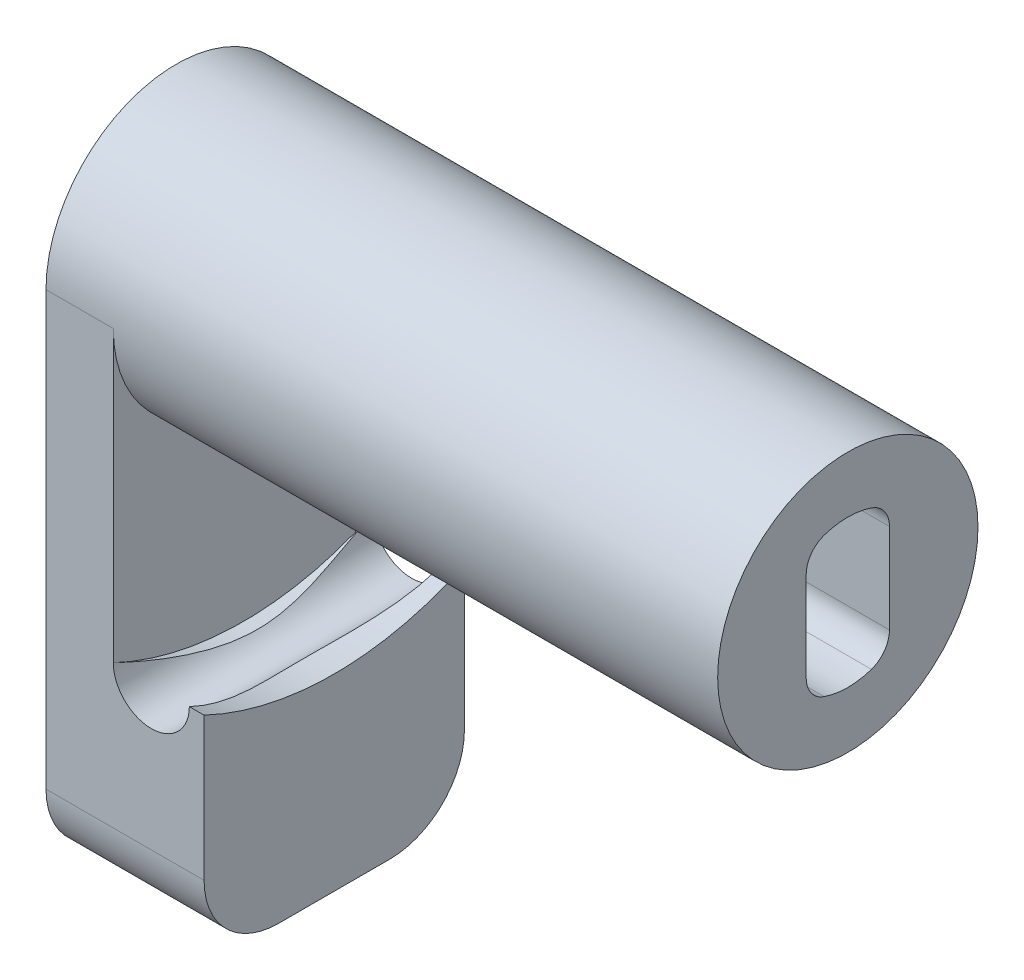
SolidWorks part; units mm, degrees
material "ABS"
ref_plane "Front Plane" through (0, 0, 0) normal (1, 0, 0) x (0, 1, 0)
ref_plane "Top Plane" through (0, 0, 0) normal (0, 0, 1) x (0, 1, 0)
ref_plane "Right Plane" through (0, 0, 0) normal (0, 1, 0) x (-1, 0, 0)
sketch "Sketch1" plane through (0, 0, 0) normal (1, 0, 0) x (0, 1, 0)
  circle A2 centre (0, 0) radius 8.7376
  dimension "D3" = 17.4752
extrude "Boss-Extrude1" add sketch "Sketch1" along normal blind 45.085
sketch "Sketch10" plane through (0, 0, 0) normal (-1, 0, 0) x (0, -1, 0)
  line L0 (0, 8.7376) -> (34.036, 8.7376)
  line L2 (34.036, 8.7376) -> (34.036, -8.7376)
  line L3 (34.036, -8.7376) -> (0, -8.7376)
  circle A0 centre (0, 0) radius 8.7376 construction
  arc A2 (0, 8.7376) -> (0, -8.7376) centre (0, 0) cw
  dimension "D1" = 34.036
extrude "Boss-Extrude3" add sketch "Sketch10" against normal blind 4.516 contours L0 A2 L3 L2
fillet "Fillet2" radius 5 2 edges at (2.258, -34.036, 8.7376) (2.258, -34.036, -8.7376)
sketch "Sketch14" [suppressed] plane through (0, 0, 0) normal (-1, 0, 0) x (0, 0, 1)
  line L0 (0.5115, -3.4237) -> (0.3944, -4.0089)
  line L1 (0, 0) -> (0, -4.064) construction
  line L2 (0, 0) -> (0.5606, -3.4335) construction
  line L3 (0.6039, -3.4087) -> (0.9011, -3.9262)
  line L4 (-0.6903, -3.3922) -> (-1.0005, -3.9021)
  line L5 (-0.5983, -3.4096) -> (-0.4961, -3.9976)
  line L6 (-1.8089, -2.9515) -> (-2.2748, -3.3245)
  line L7 (-1.7284, -2.9994) -> (-1.8334, -3.5869)
  line L8 (-2.7093, -2.1549) -> (-3.2746, -2.346)
  line L9 (-2.65, -2.2273) -> (-2.9496, -2.7435)
  line L10 (-3.2829, -1.0983) -> (-3.8795, -1.0846)
  line L11 (-3.252, -1.1867) -> (-3.7101, -1.5692)
  line L12 (-3.4605, 0.0907) -> (-4.0165, 0.3077)
  line L13 (-3.4617, -0.0029) -> (-4.023, -0.2057)
  line L14 (-3.2208, 1.2689) -> (-3.669, 1.6629)
  line L15 (-3.2539, 1.1813) -> (-3.8507, 1.1827)
  line L16 (-2.5926, 2.2939) -> (-2.879, 2.8175)
  line L17 (-2.6537, 2.223) -> (-3.214, 2.4284)
  line L18 (-1.6517, 3.0423) -> (-1.7417, 3.6323)
  line L19 (-1.7333, 2.9965) -> (-2.1896, 3.3812)
  line L20 (-0.5115, 3.4237) -> (-0.3944, 4.0089)
  line L21 (-0.6039, 3.4087) -> (-0.9011, 3.9262)
  line L22 (0.6903, 3.3922) -> (1.0005, 3.9021)
  line L23 (0.5983, 3.4096) -> (0.4961, 3.9976)
  line L24 (1.8089, 2.9515) -> (2.2748, 3.3245)
  line L25 (1.7284, 2.9994) -> (1.8334, 3.5869)
  line L26 (2.7093, 2.1549) -> (3.2746, 2.346)
  line L27 (2.65, 2.2273) -> (2.9496, 2.7435)
  line L28 (3.2829, 1.0983) -> (3.8795, 1.0846)
  line L29 (3.252, 1.1867) -> (3.7101, 1.5692)
  line L30 (3.4605, -0.0907) -> (4.0165, -0.3077)
  line L31 (3.4617, 0.0029) -> (4.023, 0.2057)
  line L32 (3.2208, -1.2689) -> (3.669, -1.6629)
  line L33 (3.2539, -1.1813) -> (3.8507, -1.1827)
  line L34 (2.5926, -2.2939) -> (2.879, -2.8175)
  line L35 (2.6537, -2.223) -> (3.214, -2.4284)
  line L36 (1.6517, -3.0423) -> (1.7417, -3.6323)
  line L37 (1.7333, -2.9965) -> (2.1896, -3.3812)
  line L38 (-0.1032, -4.0627) -> (0, -4.064)
  line L39 (-1.4865, -3.7824) -> (-1.39, -3.8189)
  line L40 (-2.6905, -3.0459) -> (-2.6123, -3.1132)
  line L41 (-3.5195, -2.032) -> (-3.57, -1.942)
  line L42 (-4.0023, -0.7057) -> (-4.0189, -0.6039)
  line L43 (-4.0023, 0.7057) -> (-3.9831, 0.8071)
  line L44 (-3.5195, 2.032) -> (-3.4668, 2.1207)
  line L45 (-2.6123, 3.1132) -> (-2.5324, 3.1785)
  line L46 (-1.39, 3.8189) -> (-1.2926, 3.853)
  line L47 (0, 4.064) -> (0.1032, 4.0627)
  line L48 (1.39, 3.8189) -> (1.4865, 3.7824)
  line L49 (2.6123, 3.1132) -> (2.6905, 3.0459)
  line L50 (3.5195, 2.032) -> (3.57, 1.942)
  line L51 (4.0023, 0.7057) -> (4.0189, 0.6039)
  line L52 (4.0023, -0.7057) -> (3.9831, -0.8071)
  line L53 (3.5195, -2.032) -> (3.4668, -2.1207)
  line L54 (2.6123, -3.1132) -> (2.5324, -3.1785)
  line L55 (1.39, -3.8189) -> (1.2926, -3.853)
  arc A0 (0.3497, -4.0489) -> (0, -4.064) centre (0, 0) cw
  arc A1 (0.3497, -4.0489) -> (0.3944, -4.0089) centre (0.3454, -3.9991) ccw
  arc A2 (0.5115, -3.4237) -> (0.6039, -3.4087) centre (0.5606, -3.4335) cw
  arc A3 (0.4203, -4.0631) -> (0.3944, -4.0089) centre (0.4434, -4.0187) cw
  arc A4 (0.4203, -4.0631) -> (0.7372, -4.2116) centre (2.3016, -0.4608) ccw
  arc A6 (0.9562, -3.9499) -> (0.9011, -3.9262) centre (0.9445, -3.9013) cw
  arc A7 (0.9562, -3.9499) -> (1.2926, -3.853) centre (0, 0) ccw
  arc A8 (-1.0562, -3.9243) -> (-1.39, -3.8189) centre (0, 0) cw
  arc A9 (-1.0562, -3.9243) -> (-1.0005, -3.9021) centre (-1.0432, -3.8761) ccw
  arc A10 (-0.6903, -3.3922) -> (-0.5983, -3.4096) centre (-0.6476, -3.4182) cw
  arc A11 (-0.4524, -4.0387) -> (-0.4961, -3.9976) centre (-0.4468, -3.9891) cw
  arc A12 (-0.4524, -4.0387) -> (-0.1032, -4.0627) centre (0, 0) ccw
  arc A13 (-2.3347, -3.3264) -> (-2.6123, -3.1132) centre (0, 0) cw
  arc A14 (-2.3347, -3.3264) -> (-2.2748, -3.3245) centre (-2.306, -3.2855) ccw
  arc A15 (-1.8089, -2.9515) -> (-1.7284, -2.9994) centre (-1.7776, -2.9906) cw
  arc A16 (-1.8064, -3.6405) -> (-1.8334, -3.5869) centre (-1.7842, -3.5957) cw
  arc A17 (-1.8064, -3.6405) -> (-1.4865, -3.7824) centre (0, 0) ccw
  arc A18 (-3.3316, -2.3273) -> (-3.5195, -2.032) centre (0, 0) cw
  arc A19 (-3.3316, -2.3273) -> (-3.2746, -2.346) centre (-3.2906, -2.2987) ccw
  arc A20 (-2.7093, -2.1549) -> (-2.65, -2.2273) centre (-2.6933, -2.2022) cw
  arc A21 (-2.9426, -2.8031) -> (-2.9496, -2.7435) centre (-2.9064, -2.7686) cw
  arc A22 (-2.9426, -2.8031) -> (-2.6905, -3.0459) centre (0, 0) ccw
  arc A23 (-3.9267, -1.0475) -> (-4.0023, -0.7057) centre (0, 0) cw
  arc A24 (-3.9267, -1.0475) -> (-3.8795, -1.0846) centre (-3.8784, -1.0346) ccw
  arc A25 (-3.2829, -1.0983) -> (-3.252, -1.1867) centre (-3.284, -1.1483) cw
  arc A26 (-3.7238, -1.6276) -> (-3.7101, -1.5692) centre (-3.678, -1.6076) cw
  arc A27 (-3.7238, -1.6276) -> (-3.57, -1.942) centre (0, 0) ccw
  arc A28 (-4.0481, 0.3587) -> (-4.0023, 0.7057) centre (0, 0) cw
  arc A29 (-4.0481, 0.3587) -> (-4.0165, 0.3077) centre (-3.9983, 0.3543) ccw
  arc A30 (-3.4605, 0.0907) -> (-3.4617, -0.0029) centre (-3.4787, 0.0442) cw
  arc A31 (-4.0559, -0.2558) -> (-4.023, -0.2057) centre (-4.006, -0.2527) cw
  arc A32 (-4.0559, -0.2558) -> (-4.0189, -0.6039) centre (0, 0) ccw
  arc A33 (-3.6813, 1.7216) -> (-3.5195, 2.032) centre (0, 0) cw
  arc A34 (-3.6813, 1.7216) -> (-3.669, 1.6629) centre (-3.636, 1.7005) ccw
  arc A35 (-3.2208, 1.2689) -> (-3.2539, 1.1813) centre (-3.2538, 1.2313) cw
  arc A36 (-3.8988, 1.1468) -> (-3.8507, 1.1827) centre (-3.8509, 1.1327) cw
  arc A37 (-3.8988, 1.1468) -> (-3.9831, 0.8071) centre (0, 0) ccw
  arc A38 (-2.8705, 2.8769) -> (-2.6123, 3.1132) centre (0, 0) cw
  arc A39 (-2.8705, 2.8769) -> (-2.879, 2.8175) centre (-2.8352, 2.8415) ccw
  arc A40 (-2.5926, 2.2939) -> (-2.6537, 2.223) centre (-2.6365, 2.2699) cw
  arc A41 (-3.2715, 2.4111) -> (-3.214, 2.4284) centre (-3.2312, 2.3815) cw
  arc A42 (-3.2715, 2.4111) -> (-3.4668, 2.1207) centre (0, 0) ccw
  arc A43 (-1.7134, 3.6852) -> (-1.39, 3.8189) centre (0, 0) cw
  arc A44 (-1.7134, 3.6852) -> (-1.7417, 3.6323) centre (-1.6923, 3.6398) ccw
  arc A45 (-1.6517, 3.0423) -> (-1.7333, 2.9965) centre (-1.7011, 3.0348) cw
  arc A46 (-2.2495, 3.3846) -> (-2.1896, 3.3812) centre (-2.2218, 3.343) cw
  arc A47 (-2.2495, 3.3846) -> (-2.5324, 3.1785) centre (0, 0) ccw
  arc A48 (-0.3497, 4.0489) -> (0, 4.064) centre (0, 0) cw
  arc A49 (-0.3497, 4.0489) -> (-0.3944, 4.0089) centre (-0.3454, 3.9991) ccw
  arc A50 (-0.5115, 3.4237) -> (-0.6039, 3.4087) centre (-0.5606, 3.4335) cw
  arc A51 (-0.9562, 3.9499) -> (-0.9011, 3.9262) centre (-0.9445, 3.9013) cw
  arc A52 (-0.9562, 3.9499) -> (-1.2926, 3.853) centre (0, 0) ccw
  arc A53 (1.0562, 3.9243) -> (1.39, 3.8189) centre (0, 0) cw
  arc A54 (1.0562, 3.9243) -> (1.0005, 3.9021) centre (1.0432, 3.8761) ccw
  arc A55 (0.6903, 3.3922) -> (0.5983, 3.4096) centre (0.6476, 3.4182) cw
  arc A56 (0.4524, 4.0387) -> (0.4961, 3.9976) centre (0.4468, 3.9891) cw
  arc A57 (0.4524, 4.0387) -> (0.1032, 4.0627) centre (0, 0) ccw
  arc A58 (2.3347, 3.3264) -> (2.6123, 3.1132) centre (0, 0) cw
  arc A59 (2.3347, 3.3264) -> (2.2748, 3.3245) centre (2.306, 3.2855) ccw
  arc A60 (1.8089, 2.9515) -> (1.7284, 2.9994) centre (1.7776, 2.9906) cw
  arc A61 (1.8064, 3.6405) -> (1.8334, 3.5869) centre (1.7842, 3.5957) cw
  arc A62 (1.8064, 3.6405) -> (1.4865, 3.7824) centre (0, 0) ccw
  arc A63 (3.3316, 2.3273) -> (3.5195, 2.032) centre (0, 0) cw
  arc A64 (3.3316, 2.3273) -> (3.2746, 2.346) centre (3.2906, 2.2987) ccw
  arc A65 (2.7093, 2.1549) -> (2.65, 2.2273) centre (2.6933, 2.2022) cw
  arc A66 (2.9426, 2.8031) -> (2.9496, 2.7435) centre (2.9064, 2.7686) cw
  arc A67 (2.9426, 2.8031) -> (2.6905, 3.0459) centre (0, 0) ccw
  arc A68 (3.9267, 1.0475) -> (4.0023, 0.7057) centre (0, 0) cw
  arc A69 (3.9267, 1.0475) -> (3.8795, 1.0846) centre (3.8784, 1.0346) ccw
  arc A70 (3.2829, 1.0983) -> (3.252, 1.1867) centre (3.284, 1.1483) cw
  arc A71 (3.7238, 1.6276) -> (3.7101, 1.5692) centre (3.678, 1.6076) cw
  arc A72 (3.7238, 1.6276) -> (3.57, 1.942) centre (0, 0) ccw
  arc A73 (4.0481, -0.3587) -> (4.0023, -0.7057) centre (0, 0) cw
  arc A74 (4.0481, -0.3587) -> (4.0165, -0.3077) centre (3.9983, -0.3543) ccw
  arc A75 (3.4605, -0.0907) -> (3.4617, 0.0029) centre (3.4787, -0.0442) cw
  arc A76 (4.0559, 0.2558) -> (4.023, 0.2057) centre (4.006, 0.2527) cw
  arc A77 (4.0559, 0.2558) -> (4.0189, 0.6039) centre (0, 0) ccw
  arc A78 (3.6813, -1.7216) -> (3.5195, -2.032) centre (0, 0) cw
  arc A79 (3.6813, -1.7216) -> (3.669, -1.6629) centre (3.636, -1.7005) ccw
  arc A80 (3.2208, -1.2689) -> (3.2539, -1.1813) centre (3.2538, -1.2313) cw
  arc A81 (3.8988, -1.1468) -> (3.8507, -1.1827) centre (3.8509, -1.1327) cw
  arc A82 (3.8988, -1.1468) -> (3.9831, -0.8071) centre (0, 0) ccw
  arc A83 (2.8705, -2.8769) -> (2.6123, -3.1132) centre (0, 0) cw
  arc A84 (2.8705, -2.8769) -> (2.879, -2.8175) centre (2.8352, -2.8415) ccw
  arc A85 (2.5926, -2.2939) -> (2.6537, -2.223) centre (2.6365, -2.2699) cw
  arc A86 (3.2715, -2.4111) -> (3.214, -2.4284) centre (3.2312, -2.3815) cw
  arc A87 (3.2715, -2.4111) -> (3.4668, -2.1207) centre (0, 0) ccw
  arc A88 (1.7134, -3.6852) -> (1.39, -3.8189) centre (0, 0) cw
  arc A89 (1.7134, -3.6852) -> (1.7417, -3.6323) centre (1.6923, -3.6398) ccw
  arc A90 (1.6517, -3.0423) -> (1.7333, -2.9965) centre (1.7011, -3.0348) cw
  arc A91 (2.2495, -3.3846) -> (2.1896, -3.3812) centre (2.2218, -3.343) cw
  arc A92 (2.2495, -3.3846) -> (2.5324, -3.1785) centre (0, 0) ccw
  point P207 (0, 0)
  dimension "D1" = 4.064
  dimension "D2" = 0.05
  dimension "D3" = 0.05
  dimension "D4" = 0.04
  dimension "D5" = 18
  dimension "D6" = 0.5968
  dimension "D8" = 0.35
sketch "Sketch15" plane through (4.516, 0, 0) normal (1, 0, 0) x (0, 1, 0)
  line L1 (-29.036, 8.7376) -> (-18.796, 8.7376)
  line L2 (-18.796, 8.7376) -> (-18.796, -8.7376)
  line L3 (0, 8.7376) -> (-29.036, 8.7376) construction
  line L4 (-29.036, -8.7376) -> (-18.796, -8.7376)
  line L5 (-34.036, 3.7376) -> (-34.036, -3.7376) construction
  line L6 (-34.036, 3.7376) -> (-34.036, -3.7376)
  line L8 (-29.036, -8.7376) -> (0, -8.7376) construction
  line L13 (0, 8.7376) -> (-29.036, 8.7376)
  line L14 (-34.036, 3.7376) -> (-34.036, -3.7376)
  line L15 (-29.036, -8.7376) -> (0, -8.7376)
  line L17 (-34.036, 3.7376) -> (-34.036, -3.7376)
  arc A0 (-29.036, 8.7376) -> (-34.036, 3.7376) centre (-29.036, 3.7376) ccw construction
  arc A1 (-34.036, -3.7376) -> (-29.036, -8.7376) centre (-29.036, -3.7376) ccw construction
  arc A2 (-29.036, 8.7376) -> (-34.036, 3.7376) centre (-29.036, 3.7376) ccw
  arc A3 (-34.036, -3.7376) -> (-29.036, -8.7376) centre (-29.036, -3.7376) ccw
  arc A7 (-29.036, 8.7376) -> (-34.036, 3.7376) centre (-29.036, 3.7376) ccw
  arc A8 (-34.036, -3.7376) -> (-29.036, -8.7376) centre (-29.036, -3.7376) ccw
  arc A9 (0, 8.7376) -> (0, -8.7376) centre (0, 0) ccw
  arc A10 (-29.036, 8.7376) -> (-34.036, 3.7376) centre (-29.036, 3.7376) ccw
  arc A11 (-34.036, -3.7376) -> (-29.036, -8.7376) centre (-29.036, -3.7376) ccw
  arc A12 (0, 8.7376) -> (0, -8.7376) centre (0, 0) ccw
  dimension "D1" = 15.24
  dimension "D2" = 0
extrude "Boss-Extrude4" add sketch "Sketch15" along normal blind 6.096
sketch "Sketch21" plane through (10.612, 0, 0) normal (1, 0, 0) x (0, 1, 0)
  line L2 (-18.796, -8.7376) -> (-18.796, 8.7376)
  line L4 (-29.036, 8.7376) -> (-18.796, 8.7376) construction
  line L5 (-19.431, -8.7376) -> (-18.796, -8.7376)
  line L6 (-18.796, 8.7376) -> (-18.796, -8.7376) construction
  line L8 (-18.796, -8.7376) -> (0, -8.7376) construction
  line L14 (-18.796, -8.7376) -> (-18.796, 8.7376) construction
  line L20 (-18.796, 8.7376) -> (-29.036, 8.7376)
  arc A2 (-19.431, -8.7376) -> (-19.431, 8.7376) centre (-1.0855, 0) cw
  dimension "D4" = 20.32
  dimension "D2" = 0.635
  dimension "D3" = 0.635
extrude "Cut-Extrude8" cut sketch "Sketch21" against normal up to surface (6.096 mm away)
sketch "Sketch22" plane through (45.085, 0, 0) normal (1, 0, 0) x (0, 1, 0)
  line L7 (-4.0897, -2.794) -> (4.0897, 2.794) construction
  line L8 (-4.0897, 2.794) -> (4.0897, -2.794) construction
  line L11 (-4.0897, -2.794) -> (4.0897, -2.794)
  line L13 (-4.0897, 2.794) -> (4.0897, 2.794)
  line L15 (-4.0897, -2.794) -> (4.0897, 2.794) construction
  line L16 (-4.0897, 2.794) -> (4.0897, -2.794) construction
  arc A3 (-4.0897, 2.794) -> (-4.0897, -2.794) centre (0, 0) ccw
  arc A4 (4.0897, -2.794) -> (4.0897, 2.794) centre (0, 0) ccw
  dimension "D2" = 9.906
  dimension "D3" = 5.588
extrude "Cut-Extrude10" cut sketch "Sketch22" against normal blind 12.192
fillet "Fillet11" radius 1.778 4 edges at (38.989, 4.0897, -2.794) (38.989, 4.0897, 2.794) (38.989, -4.0897, -2.794) (38.989, -4.0897, 2.794)
sketch "Sketch25" plane through (0, 0, -8.7376) normal (0, 0, -1) x (1, 0, 0)
  line L3 (4.516, 19.431) -> (4.516, 0) construction
  line L4 (4.516, 19.431) -> (10.612, 19.431) construction
  circle A0 centre (7.0687, 19.431) radius 2.5527
  dimension "D1" = 5.1054
extrude "Cut-Extrude14" cut sketch "Sketch25" against normal through all
sketch "Sketch26" plane through (0, 0, 0) normal (-1, 0, 0) x (0, -1, 0)
  line L1 (3.6846, 1.7145) -> (5.5896, 1.7145)
  line L2 (3.6846, 1.7145) -> (3.6846, -1.7145) construction
  line L3 (3.6846, -1.7145) -> (5.5896, -1.7145)
  line L4 (5.5896, 1.7145) -> (5.5896, -1.7145)
  arc A0 (3.6846, 1.7145) -> (3.6846, -1.7145) centre (0, 0) ccw
  dimension "D1" = 8.128
  dimension "D2" = 3.429
  dimension "D3" = 1.905
extrude "Cut-Extrude15" cut sketch "Sketch26" against normal blind 21.59
fillet "Fillet12" radius 0.3969 4 edges at (10.795, -3.6846, 1.7145) (10.795, -5.5896, 1.7145) (10.795, -3.6846, -1.7145) (10.795, -5.5896, -1.7145)
